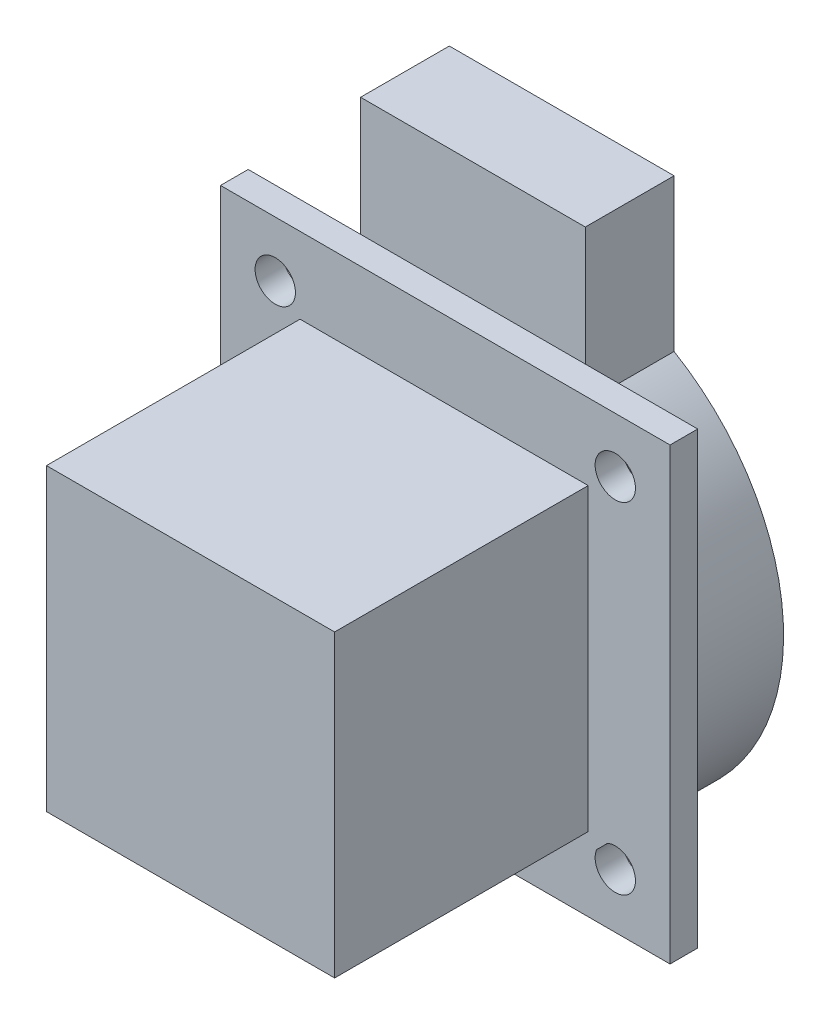
SolidWorks part; units mm, degrees
ref_plane "Front Plane" through (0, 0, 0) normal (0, 0, 1) x (1, 0, 0)
ref_plane "Top Plane" through (0, 0, 0) normal (0, 1, 0) x (1, 0, 0)
ref_plane "Right Plane" through (0, 0, 0) normal (1, 0, 0) x (0, 0, -1)
sketch "Sketch1" plane through (0, 0, 0) normal (0, 0, 1) x (1, 0, 0)
  line L1 (0, 0) -> (49.53, 0)
  line L2 (0, 0) -> (0, 49.53)
  line L3 (0, 49.53) -> (49.53, 49.53)
  line L4 (49.53, 0) -> (49.53, 49.53)
  line L5 (24.765, 49.53) -> (24.765, 0) construction
  line L6 (0, 24.765) -> (49.53, 24.765) construction
  point P60 (24.765, 24.765)
  dimension "D1" = 49.53
extrude "Boss-Extrude1" add sketch "Sketch1" along normal blind 3.048
sketch "Sketch2" plane through (0, 0, 0) normal (0, 0, -1) x (-1, 0, 0)
  line L0 (-24.765, 49.53) -> (-12.3825, 49.53)
  line L1 (-49.53, 49.53) -> (0, 49.53)
  line L2 (-49.53, 49.53) -> (-49.53, 0)
  line L3 (-49.53, 0) -> (0, 0)
  line L4 (0, 49.53) -> (0, 0)
  line L5 (-24.765, 0) -> (-24.765, 49.53) construction
  line L6 (-49.53, 24.765) -> (0, 24.765) construction
  line L7 (-37.1475, 49.53) -> (-37.1475, 45.8447)
  line L8 (-12.3825, 49.53) -> (-37.1475, 49.53)
  line L9 (-12.3825, 49.53) -> (-12.3825, 62.611)
  line L10 (-12.3825, 62.611) -> (-37.1475, 62.611)
  line L11 (-37.1475, 49.53) -> (-37.1475, 62.611)
  line L12 (-24.765, 62.611) -> (-24.765, 49.53) construction
  line L13 (-12.3825, 56.0705) -> (-37.1475, 56.0705) construction
  line L14 (-12.3825, 49.53) -> (-12.3825, 45.8447)
  circle A0 centre (-24.765, 24.765) radius 24.4475
  point P88 (-24.765, 24.765)
  point P93 (-24.765, 56.0705)
  line M2 (0, 49.53) -> (-49.53, 49.53)
  dimension "D1" = 48.895
  dimension "D2" = 12.3825
  dimension "D3" = 13.081
  dimension "D4" = 24.765
extrude "Boss-Extrude2" add sketch "Sketch2" along normal blind 9.779 contours L11 L9 L10 M2 | A0 L14 L7 M2 | A0
sketch "Sketch3" plane through (0, 0, 0) normal (0, 0, -1) x (-1, 0, 0)
  line L1 (-49.53, 49.53) -> (-43.4975, 49.53)
  line L2 (-49.53, 49.53) -> (-49.53, 43.4975)
  line L3 (-49.53, 43.4975) -> (-43.4975, 43.4975)
  line L4 (-43.4975, 49.53) -> (-43.4975, 43.4975)
  line L5 (-46.5137, 43.4975) -> (-46.5137, 49.53) construction
  line L6 (-49.53, 46.5137) -> (-43.4975, 46.5137) construction
  line L7 (-49.53, 0) -> (-43.4975, 0)
  line L8 (-49.53, 0) -> (-49.53, 6.0325)
  line L9 (-49.53, 6.0325) -> (-43.4975, 6.0325)
  line L10 (-43.4975, 0) -> (-43.4975, 6.0325)
  line L11 (-46.5137, 6.0325) -> (-46.5137, 0) construction
  line L12 (-49.53, 3.0162) -> (-43.4975, 3.0162) construction
  line L13 (0, 0) -> (-6.096, 0)
  line L14 (0, 0) -> (0, 6.0325)
  line L15 (0, 6.0325) -> (-6.096, 6.0325)
  line L16 (-6.096, 0) -> (-6.096, 6.0325)
  line L17 (-3.048, 6.0325) -> (-3.048, 0) construction
  line L18 (0, 3.0162) -> (-6.096, 3.0162) construction
  line L19 (0, 49.53) -> (-6.0325, 49.53)
  line L20 (0, 49.53) -> (0, 43.434)
  line L21 (0, 43.434) -> (-6.0325, 43.434)
  line L22 (-6.0325, 49.53) -> (-6.0325, 43.434)
  line L23 (-3.0162, 43.434) -> (-3.0162, 49.53) construction
  line L24 (0, 46.482) -> (-6.0325, 46.482) construction
  circle A0 centre (-43.4975, 43.4975) radius 2.2225
  circle A1 centre (-6.0325, 43.434) radius 2.2225
  circle A2 centre (-6.096, 6.0325) radius 2.2225
  circle A3 centre (-43.4975, 6.0325) radius 2.2225
  point P40 (-46.5137, 46.5137)
  point P51 (-46.5137, 3.0162)
  point P73 (-3.048, 3.0162)
  point P91 (-3.0162, 46.482)
  arc M1 (-12.3825, 45.8447) -> (-37.1475, 45.8447) centre (-24.765, 24.765) cw
  dimension "D3" = 4.445
  dimension "D9" = 4.445
  dimension "D10" = 4.445
  dimension "D11" = 4.445
  dimension "D1" = 6.0325
  dimension "D2" = 6.0325
  dimension "D4" = 6.0325
  dimension "D5" = 6.0325
  dimension "D6" = 6.096
  dimension "D7" = 6.096
  dimension "D8" = 6.0325
extrude "Cut-Extrude1" cut sketch "Sketch3" against normal blind 9.779 contours A3 L9 L10 M1 | L9 A3 L10 | L15 A2 L16 M1 | L16 A2 L15 | A1 | A0
sketch "Sketch4" plane through (0, 0, 3.048) normal (0, 0, 1) x (1, 0, 0)
  line L1 (0, 49.53) -> (49.53, 49.53)
  line L2 (0, 49.53) -> (0, 0)
  line L3 (0, 0) -> (49.53, 0)
  line L4 (49.53, 49.53) -> (49.53, 0)
  line L5 (24.765, 0) -> (24.765, 49.53) construction
  line L6 (0, 24.765) -> (49.53, 24.765) construction
  line L7 (49.53, 49.53) -> (40.513, 49.53)
  line L8 (49.53, 49.53) -> (49.53, 41.148)
  line L9 (49.53, 41.148) -> (40.513, 41.148)
  line L10 (40.513, 49.53) -> (40.513, 41.148)
  line L11 (45.0215, 41.148) -> (45.0215, 49.53) construction
  line L12 (49.53, 45.339) -> (40.513, 45.339) construction
  line L13 (40.513, 41.148) -> (8.763, 41.148)
  line L14 (40.513, 41.148) -> (40.513, 8.128)
  line L15 (40.513, 8.128) -> (8.763, 8.128)
  line L16 (8.763, 41.148) -> (8.763, 8.128)
  line L17 (24.638, 8.128) -> (24.638, 41.148) construction
  line L18 (40.513, 24.638) -> (8.763, 24.638) construction
  point P86 (45.0215, 45.339)
  point P93 (24.638, 24.638)
  point P140 (24.765, 24.765)
  dimension "D1" = 8.382
  dimension "D2" = 9.017
  dimension "D3" = 33.02
  dimension "D4" = 31.75
extrude "Boss-Extrude3" add sketch "Sketch4" along normal blind 27.94 contours L13 L16 L15 L14
